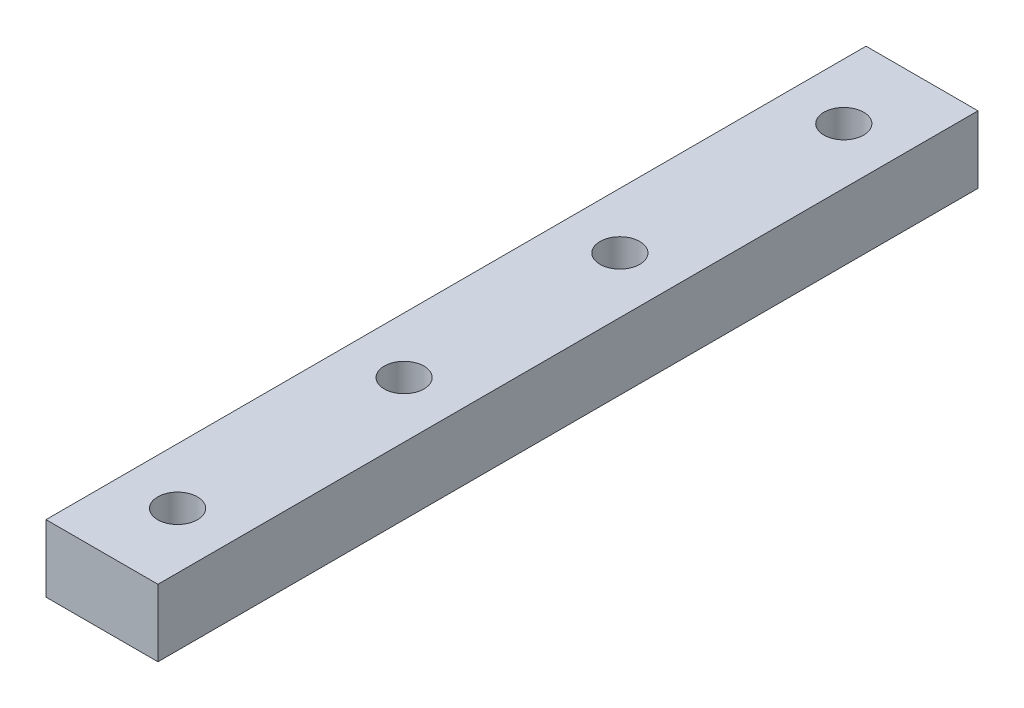
SolidWorks part; units mm, degrees
material "AISI 1020"
ref_plane "Front Plane" through (0, 0, 0) normal (0, 0, 1) x (1, 0, 0)
ref_plane "Top Plane" through (0, 0, 0) normal (0, 1, 0) x (1, 0, 0)
ref_plane "Right Plane" through (0, 0, 0) normal (1, 0, 0) x (0, 0, -1)
sketch "Sketch1" plane through (0, 0, 0) normal (0, 1, 0) x (1, 0, 0)
  line L0 (-10, 73.25) -> (10, -73.25) construction
  line L1 (-10, 73.25) -> (10, 73.25)
  line L2 (-10, 73.25) -> (-10, -73.25)
  line L3 (-10, -73.25) -> (10, -73.25)
  line L4 (10, 73.25) -> (10, -73.25)
  dimension "D1" = 20
  dimension "D2" = 146.5
extrude "Boss-Extrude1" add sketch "Sketch1" along normal blind 12
hole_wizard "Ø7.1 (7.1) Diameter Hole1" positions "Sketch2" profile "Sketch3" hole size "Ø7.1" standard "ISO" end condition through all
sketch "Sketch2" plane through (0, 12, 0) normal (0, 1, 0) x (1, 0, 0)
  line L0 (0, 19.275) -> (0, -19.275) construction
  point P0 (0, 59.275)
  point P2 (0, 19.275)
  point P4 (0, -19.275)
  point P6 (0, -59.745)
  dimension "D1" = 38.55
  dimension "D2" = 40.47
  dimension "D3" = 40
sketch "Sketch3" plane through (0, 12, -59.275) normal (1, 0, 0) x (0, 0, 1)
  line L0 (0, 0) -> (0, 12)
  line L1 (0, 12) -> (3.55, 12)
  line L2 (3.55, 12) -> (3.55, 0)
  line L5 (3.55, 0) -> (0, 0)
  line L11 (0, -6.35) -> (0, 107.95) construction
  dimension "Thru Hole Dia." = 7.1
  dimension "Thru Hole Depth" = 12
